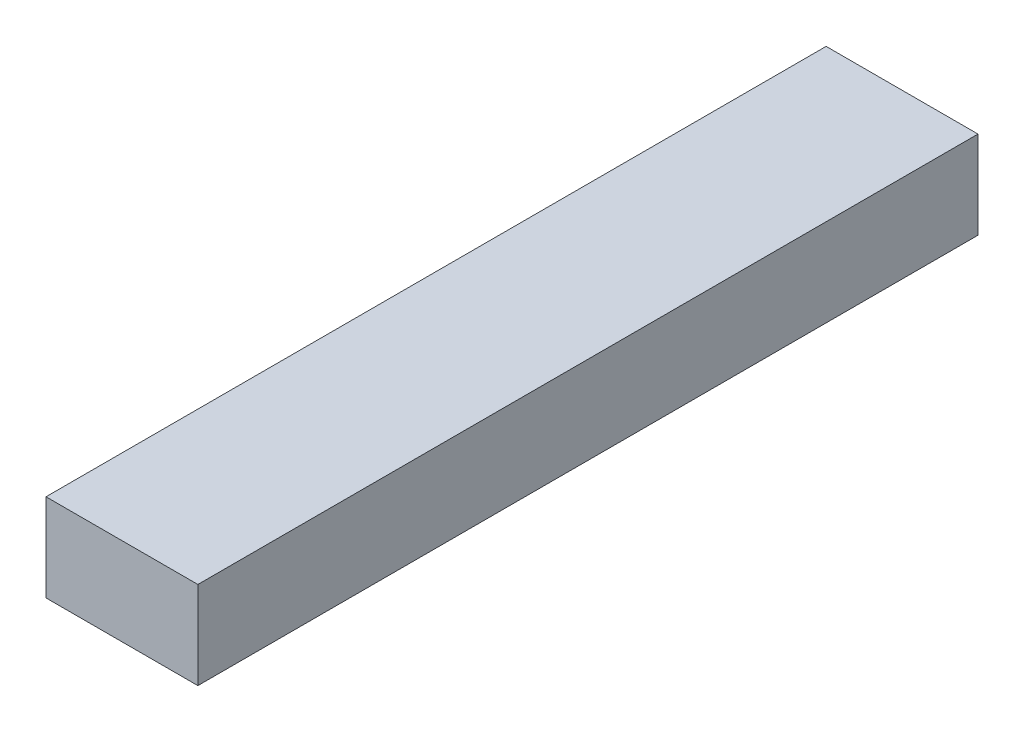
SolidWorks part; units mm, degrees
ref_plane "Front Plane" through (0, 0, 0) normal (0, 0, 1) x (1, 0, 0)
ref_plane "Top Plane" through (0, 0, 0) normal (0, 1, 0) x (1, 0, 0)
ref_plane "Right Plane" through (0, 0, 0) normal (1, 0, 0) x (0, 0, -1)
sketch "Base Sketch" plane through (0, 15, 0) normal (0, 1, 0) x (1, 0, 0)
  line L0 (15.57, 53) -> (20.57, 53) construction
  line L1 (15.57, 79.71) -> (20.57, 79.71) construction
  line L2 (15.57, 79.71) -> (15.57, 53) construction
  line L3 (15.57, 53) -> (20.57, 53) construction
  line L4 (20.57, 79.71) -> (20.57, 53) construction
  line L5 (20.57, 79.71) -> (15.57, 79.71) construction
  line L6 (15.57, 79.71) -> (15.57, 77.91) construction
  line L7 (20.57, 77.91) -> (20.57, 79.71) construction
  line L8 (15.57, 79.71) -> (13.07, 79.71) construction
  line L9 (15.47, 79.71) -> (20.67, 79.71)
  line L10 (15.47, 79.71) -> (15.47, 53)
  line L11 (15.47, 53) -> (20.67, 53)
  line L12 (20.67, 79.71) -> (20.67, 53)
  line L13 (20.57, 53) -> (23.07, 53) construction
  dimension "D1" = 0.1
  dimension "D2" = 0.1
extrude "Base Sketch Extrude" add sketch "Base Sketch" along normal blind 3
